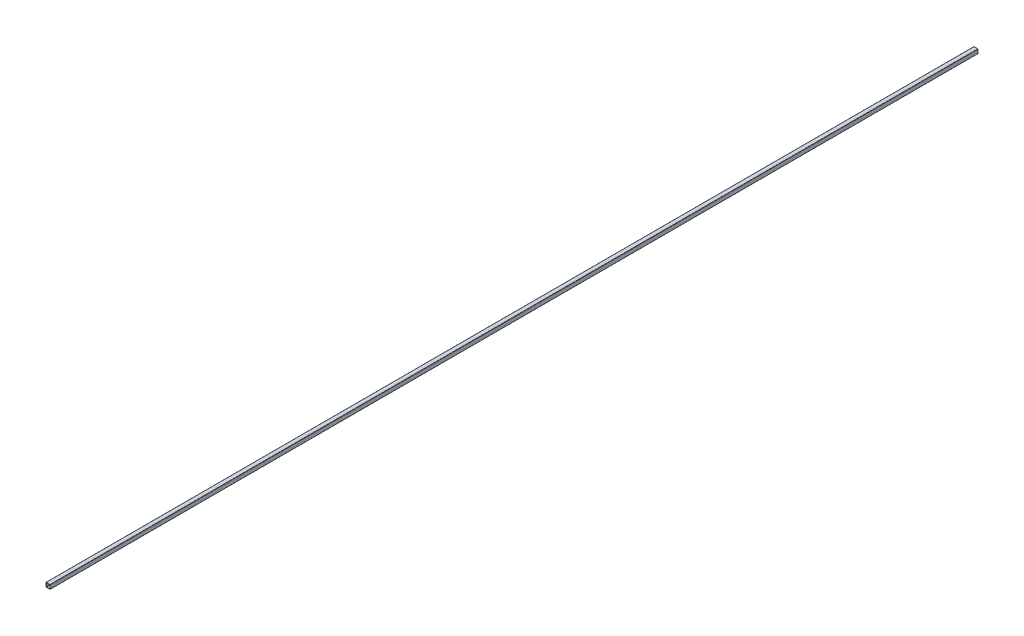
SolidWorks part; units mm, degrees
material "ASTM A500 Grade B"
ref_plane "Front Plane" through (0, 0, 0) normal (0, 0, 1) x (1, 0, 0)
ref_plane "Top Plane" through (0, 0, 0) normal (0, 1, 0) x (1, 0, 0)
ref_plane "Right Plane" through (0, 0, 0) normal (1, 0, 0) x (0, 0, -1)
sketch "Sketch1" plane through (0, 0, 0) normal (0, 0, 1) x (1, 0, 0)
  line L0 (5.3086, -2.7686) -> (32.7914, -2.7686)
  line L1 (2.54, 0) -> (35.56, 0)
  line L2 (0, -2.54) -> (0, -35.56)
  line L3 (2.54, -38.1) -> (35.56, -38.1)
  line L4 (38.1, -2.54) -> (38.1, -35.56)
  line L5 (35.3314, -5.3086) -> (35.3314, -32.7914)
  line L6 (5.3086, -35.3314) -> (32.7914, -35.3314)
  line L7 (2.7686, -5.3086) -> (2.7686, -32.7914)
  line L8 (0, 0) -> (0, -38.1) construction
  line L9 (0, -38.1) -> (38.1, -38.1) construction
  line L10 (38.1, 0) -> (38.1, -38.1) construction
  line L11 (2.7686, -2.7686) -> (2.7686, -35.3314) construction
  line L12 (2.7686, -35.3314) -> (35.3314, -35.3314) construction
  line L13 (35.3314, -2.7686) -> (35.3314, -35.3314) construction
  line L14 (2.7686, -2.7686) -> (35.3314, -2.7686) construction
  line L15 (0, 0) -> (38.1, 0) construction
  arc A0 (0, -35.56) -> (2.54, -38.1) centre (2.54, -35.56) ccw
  arc A1 (38.1, -35.56) -> (35.56, -38.1) centre (35.56, -35.56) cw
  arc A2 (2.7686, -32.7914) -> (5.3086, -35.3314) centre (5.3086, -32.7914) ccw
  arc A3 (32.7914, -35.3314) -> (35.3314, -32.7914) centre (32.7914, -32.7914) ccw
  arc A4 (35.3314, -5.3086) -> (32.7914, -2.7686) centre (32.7914, -5.3086) ccw
  arc A5 (38.1, -2.54) -> (35.56, 0) centre (35.56, -2.54) ccw
  arc A6 (0, -2.54) -> (2.54, 0) centre (2.54, -2.54) cw
  arc A7 (5.3086, -2.7686) -> (2.7686, -5.3086) centre (5.3086, -5.3086) ccw
  point P12 (0, -38.1)
  dimension "D4" = 2.54
  dimension "D3" = 2.7686
extrude "Boss-Extrude1" add sketch "Sketch1" along normal blind 8380
